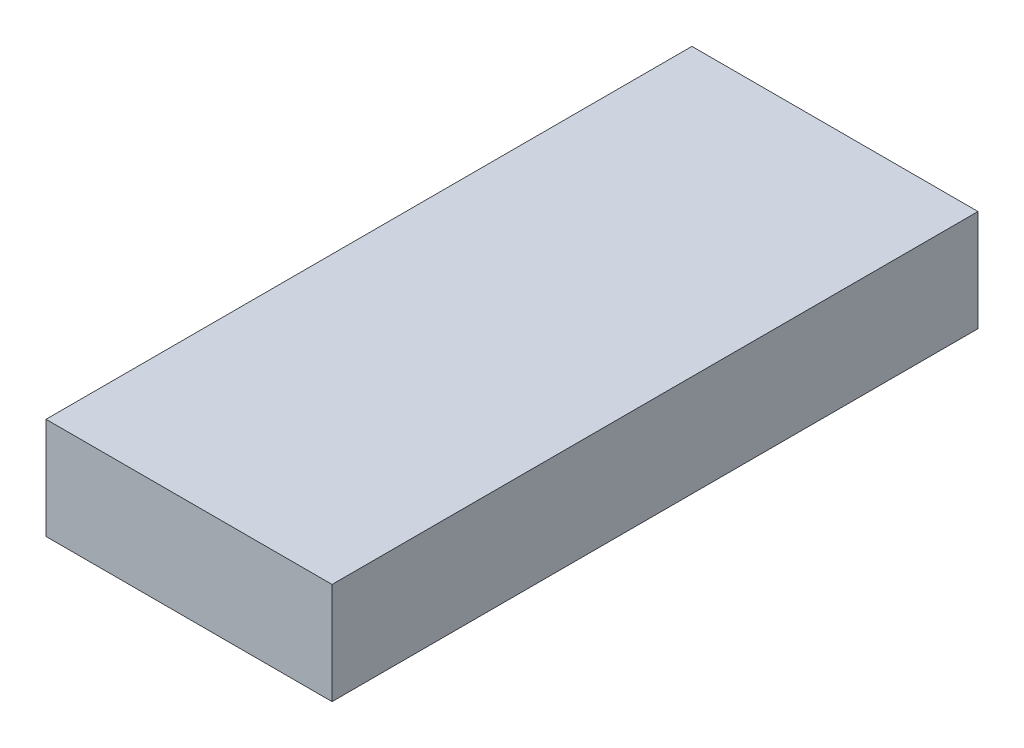
SolidWorks part; units mm, degrees
ref_plane "Front Plane" through (0, 0, 0) normal (0, 0, 1) x (1, 0, 0)
ref_plane "Top Plane" through (0, 0, 0) normal (0, 1, 0) x (1, 0, 0)
ref_plane "Right Plane" through (0, 0, 0) normal (1, 0, 0) x (0, 0, -1)
sketch "Sketch1" plane through (0, 0, 0) normal (0, 0, 1) x (1, 0, 0)
  line L1 (0, 0) -> (-31, 0)
  line L2 (0, 0) -> (0, 11)
  line L3 (0, 11) -> (-31, 11)
  line L4 (-31, 0) -> (-31, 11)
  dimension "D1" = 31
  dimension "D2" = 11
extrude "Boss-Extrude1" add sketch "Sketch1" along normal blind 70
